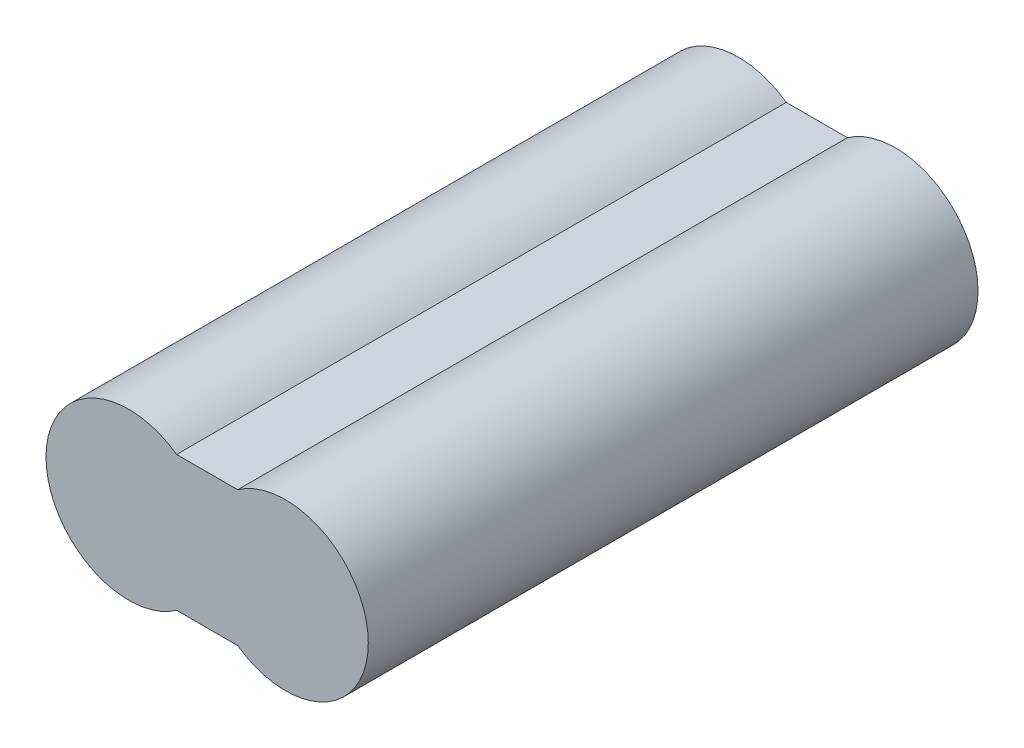
SolidWorks part; units mm, degrees
ref_plane "Front Plane" through (0, 0, 0) normal (0, 0, 1) x (1, 0, 0)
ref_plane "Top Plane" through (0, 0, 0) normal (0, 1, 0) x (1, 0, 0)
ref_plane "Right Plane" through (0, 0, 0) normal (1, 0, 0) x (0, 0, -1)
sketch "Sketch1" plane through (0, 0, 0) normal (0, 0, 1) x (1, 0, 0)
  arc A0 (9, 3.0414) -> (9, -3.0414) centre (0, 0) ccw
  arc A1 (9, -3.0414) -> (9, 3.0414) centre (18, 0) ccw
  point P4 (0, 0)
  dimension "D1" = 19
  dimension "D2" = 18
extrude "Boss-Extrude1" add sketch "Sketch1" against normal blind 70
sketch "Sketch2" plane through (0, 0, 0) normal (0, 0, 1) x (1, 0, 0)
  line L0 (9, 3.0414) -> (9, -3.0414) construction
  line L2 (5.4943, 7.75) -> (12.5057, 7.75)
  line L3 (5.4943, 7.75) -> (5.4943, -7.75)
  line L4 (5.4943, -7.75) -> (12.5057, -7.75)
  line L5 (12.5057, 7.75) -> (12.5057, -7.75)
  line L6 (5.4943, 7.75) -> (12.5057, -7.75) construction
  line L7 (5.4943, -7.75) -> (12.5057, 7.75) construction
  arc A0 (9, -3.0414) -> (9, 3.0414) centre (18, 0) ccw construction
  point P2 (9, 0)
  dimension "D1" = 15.5
extrude "Boss-Extrude2" add sketch "Sketch2" against normal up to surface (70 mm away) up to face at (9, 0, -70)
